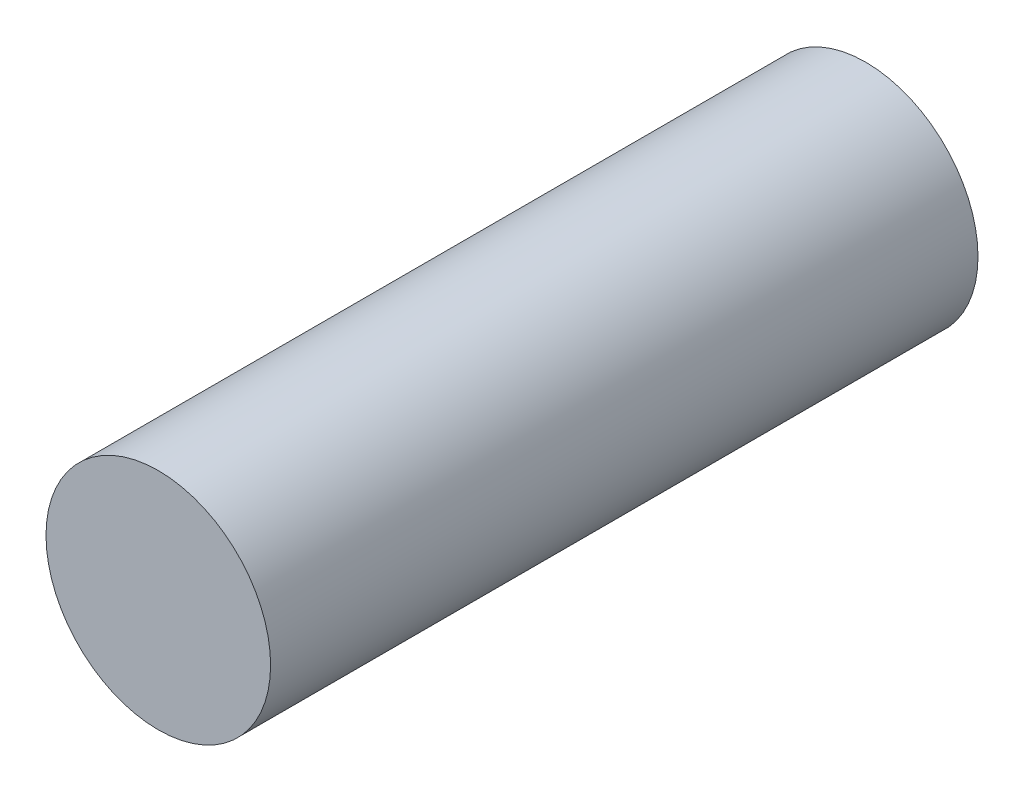
SolidWorks part; units mm, degrees
material "Alloy Steel"
ref_plane "Front Plane" through (0, 0, 0) normal (0, 0, 1) x (1, 0, 0)
ref_plane "Top Plane" through (0, 0, 0) normal (0, 1, 0) x (1, 0, 0)
ref_plane "Right Plane" through (0, 0, 0) normal (1, 0, 0) x (0, 0, -1)
sketch "Sketch1" plane through (0, 0, 0) normal (0, 0, 1) x (1, 0, 0)
  circle A0 centre (0, 0) radius 6.35
  dimension "D1" = 12.7
extrude "Boss-Extrude1" add sketch "Sketch1" along normal blind 40
